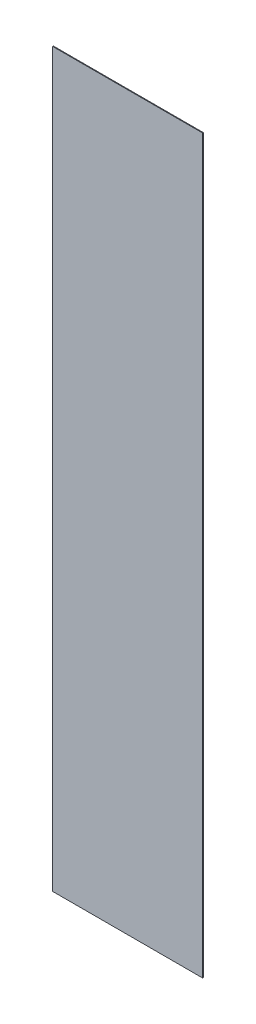
SolidWorks part; units mm, degrees
material "Клен"
ref_plane "Спереди" through (0, 0, 0) normal (0, 0, 1) x (1, 0, 0)
ref_plane "Сверху" through (0, 0, 0) normal (0, 1, 0) x (1, 0, 0)
ref_plane "Справа" through (0, 0, 0) normal (1, 0, 0) x (0, 0, -1)
sketch "Эскиз1" plane through (0, 0, 0) normal (0, 0, 1) x (1, 0, 0)
  line L1 (0, 0) -> (420, 0)
  line L2 (0, 0) -> (0, 2050)
  line L3 (0, 2050) -> (420, 2050)
  line L4 (420, 0) -> (420, 2050)
  dimension "D1" = 2050
  dimension "D2" = 420
extrude "Бобышка-Вытянуть1" add sketch "Эскиз1" along normal blind 2
